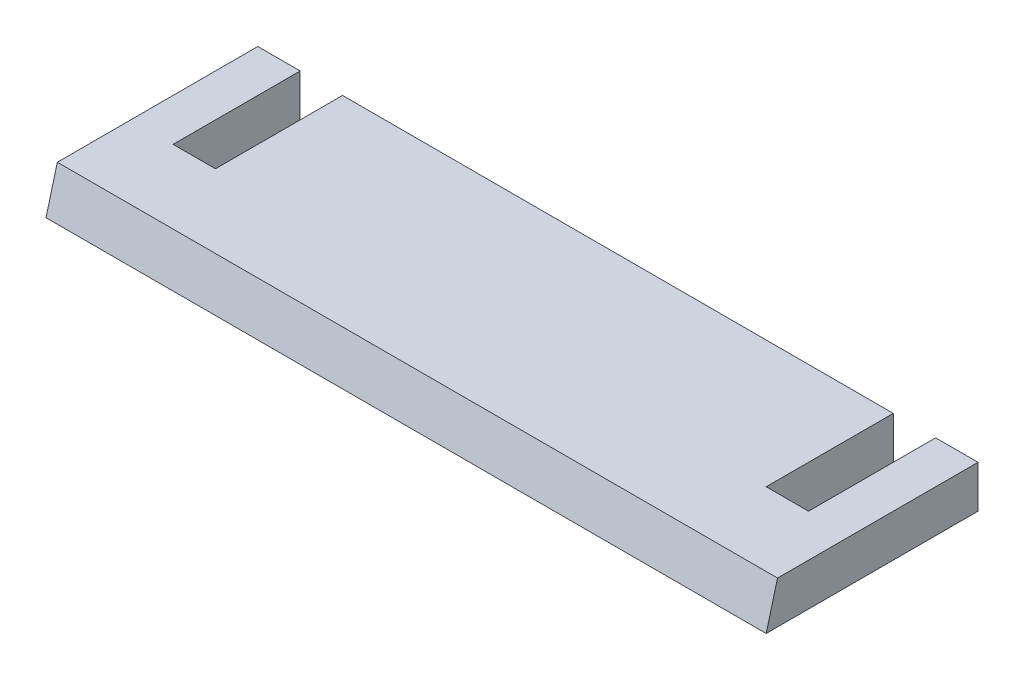
SolidWorks part; units mm, degrees
ref_plane "Front Plane" through (0, 0, 0) normal (0, 0, 1) x (1, 0, 0)
ref_plane "Top Plane" through (0, 0, 0) normal (0, 1, 0) x (1, 0, 0)
ref_plane "Right Plane" through (0, 0, 0) normal (1, 0, 0) x (0, 0, -1)
sketch "Sketch1" plane through (0, 0, 0) normal (0, 1, 0) x (1, 0, 0)
  line L0 (0, 0) -> (0, 50)
  line L1 (0, 50) -> (10, 50)
  line L2 (10, 50) -> (10, 20)
  line L3 (10, 20) -> (20, 20)
  line L4 (20, 20) -> (20, 50)
  line L5 (20, 50) -> (150, 50)
  line L6 (150, 50) -> (150, 20)
  line L7 (150, 20) -> (160, 20)
  line L8 (160, 20) -> (160, 50)
  line L9 (160, 50) -> (170, 50)
  line L10 (170, 50) -> (170, 0)
  line L11 (170, 0) -> (0, 0)
  dimension "D1" = 170
  dimension "D2" = 10
extrude "Boss-Extrude1" add sketch "Sketch1" along normal blind 10
draft "Draft1" type of draft neutral plane draft angle 15 faces to draft 1 face at (85, 5, 0) neutral plane through (0, 0, 0) neutral plane normal (0, -1, 0) reverse direction yes parameters "D1"=15
